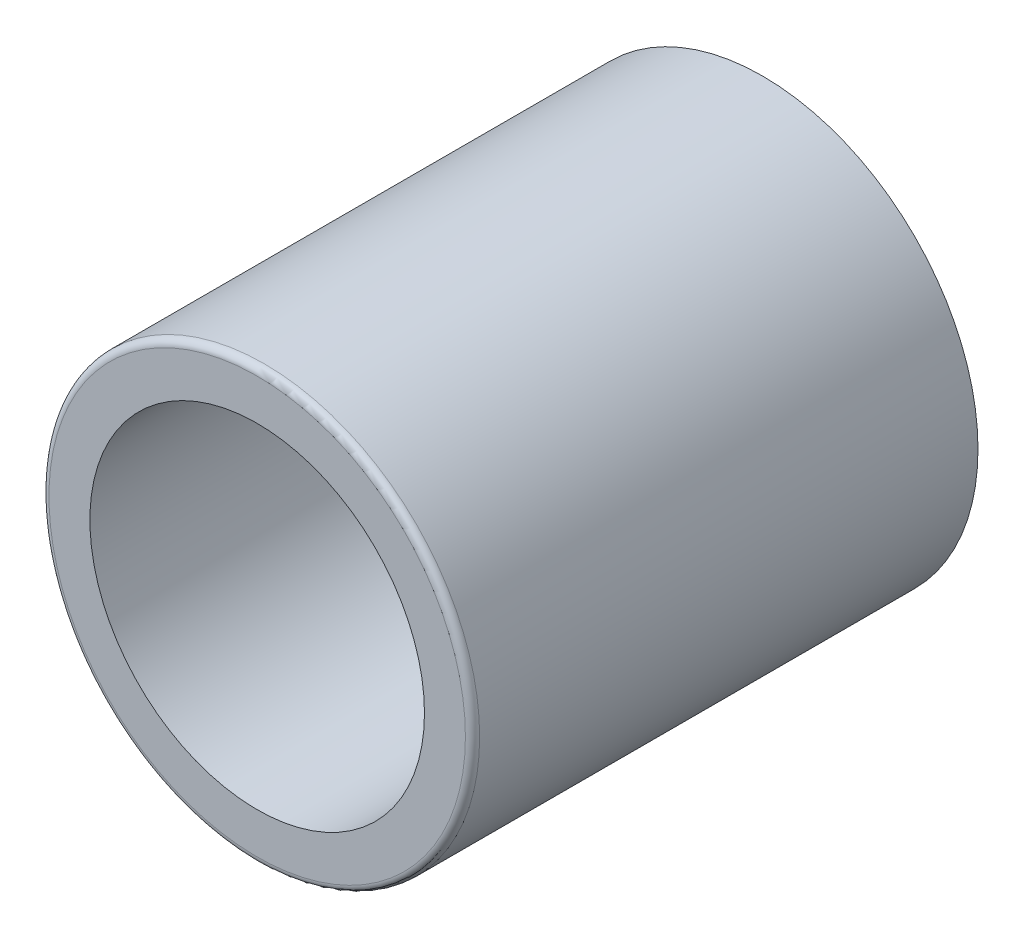
SolidWorks part; units mm, degrees
ref_plane "Alzado" through (0, 0, 0) normal (0, 0, 1) x (1, 0, 0)
ref_plane "Planta" through (0, 0, 0) normal (0, 1, 0) x (1, 0, 0)
ref_plane "Vista lateral" through (0, 0, 0) normal (1, 0, 0) x (0, 0, -1)
sketch "Croquis1" plane through (0, 0, 0) normal (0, 0, 1) x (1, 0, 0)
  circle A0 centre (0, 0) radius 6.05
  circle A1 centre (0, 0) radius 4.7
  dimension "D1" = 12.1
  dimension "D2" = 9.4
  dimension "D3" = 1.35
extrude "Saliente-Extruir1" add sketch "Croquis1" along normal blind 14.2
fillet "Redondeo1" radius 0.2 1 edges at (6.05, 0, 14.2)
